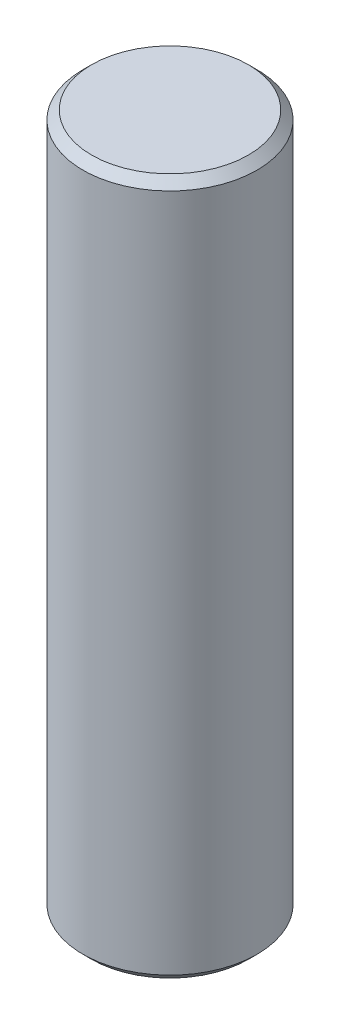
SolidWorks part; units mm, degrees
ref_plane "Front Plane" through (0, 0, 0) normal (0, 0, 1) x (1, 0, 0)
ref_plane "Top Plane" through (0, 0, 0) normal (0, 1, 0) x (1, 0, 0)
ref_plane "Right Plane" through (0, 0, 0) normal (1, 0, 0) x (0, 0, -1)
sketch "Sketch1" plane through (0, 0, 0) normal (0, 0, 1) x (1, 0, 0)
  line L0 (0, 0) -> (0, 40)
  line L1 (0, 40) -> (5, 40)
  line L2 (5, 40) -> (5, 0)
  line L3 (5, 0) -> (0, 0)
  line L4 (0, 0) -> (0, 66.175) construction
  dimension "D1" = 5
  dimension "D2" = 40
revolve "Revolve1" add sketch "Sketch1" angle 360 about L4
chamfer "Chamfer1" distance 0.5 angle 45 2 edges at (5, 0, 0) (5, 40, 0)
